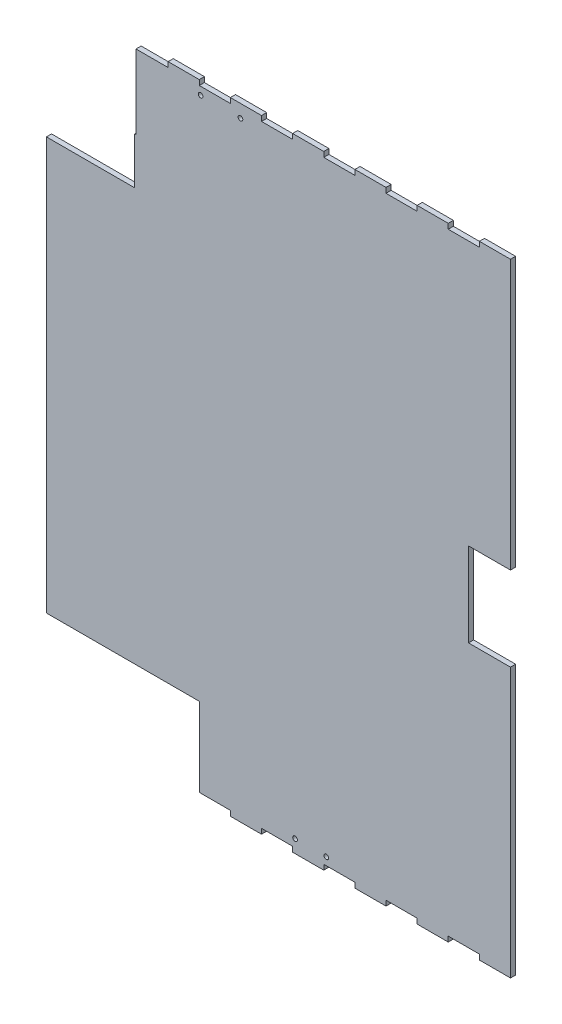
SolidWorks part; units mm, degrees
material "Balsa"
ref_plane "Front Plane" through (0, 0, 0) normal (0, 0, 1) x (1, 0, 0)
ref_plane "Top Plane" through (0, 0, 0) normal (0, 1, 0) x (1, 0, 0)
ref_plane "Right Plane" through (0, 0, 0) normal (1, 0, 0) x (0, 0, -1)
sketch "Sketch1" plane through (0, 0, 0) normal (0, 0, 1) x (1, 0, 0)
  line L0 (-5.7823, -13) -> (25.5, -13)
  line L2 (-5.7823, 1) -> (-5.7823, -13)
  line L5 (24.5, -14) -> (-24.5, -14) construction
  line L6 (323.7481, -265) -> (323.7481, 30)
  line L7 (-5.8246, -265) -> (65.6329, -265)
  line L8 (-5.8246, -265) -> (-5.8246, -225)
  line L11 (-5.8246, -265) -> (65.6329, -225) construction
  line L12 (-5.8246, -225) -> (65.6329, -265) construction
  line L15 (323.7481, -265) -> (25.5, -265)
  line L16 (25.5, 1) -> (25.5, -265)
  line L17 (-5.8246, -225) -> (25.5, -225)
  line L18 (-24.5, -224) -> (24.5, -224) construction
  line L19 (-5.7823, 1) -> (25.5, 1)
  line L20 (24.5, -224) -> (24.5, -14) construction
  line L21 (-85.1981, 31) -> (50.7481, 31) construction
  line L23 (25.5, 1) -> (25.5, 30)
  line L24 (25.5, 30) -> (323.7481, 30)
  line L27 (277.3251, 57) -> (277.3251, -295) construction
  line L28 (26.2777, -266) -> (-26.2882, -266) construction
  line L30 (-63.4467, 81) -> (255.5737, 81) construction
  line L31 (83.0863, 30) -> (323.7481, 30)
  line L32 (83.0863, 30) -> (83.0863, 77.7)
  line L33 (83.0863, 77.7) -> (323.7481, 77.7)
  line L34 (323.7481, 30) -> (323.7481, 77.7)
  line L35 (83.0863, 30) -> (323.7481, 77.7) construction
  line L36 (83.0863, 77.7) -> (323.7481, 30) construction
  line L37 (255.5737, -319) -> (-63.4467, -319) construction
  line L38 (323.7481, -265) -> (123.7481, -265)
  line L39 (323.7481, -265) -> (323.7481, -315.7)
  line L40 (323.7481, -315.7) -> (123.7481, -315.7)
  line L41 (123.7481, -265) -> (123.7481, -315.7)
  line L42 (323.7481, -265) -> (123.7481, -315.7) construction
  line L43 (323.7481, -315.7) -> (123.7481, -265) construction
  line L44 (50.7481, 31) -> (50.7481, -269) construction
  line L45 (83.0863, 31) -> (83.0863, -269) construction
  point P4 (32.4695, -6)
  point P10 (29.9042, -245)
  point P15 (48.1318, -132)
  point P24 (48.1318, 15.5)
  point P36 (203.4172, 53.85)
  point P42 (223.7481, -290.35)
  dimension "D1" = 1
  dimension "D2" = 1
  dimension "D3" = 1
  dimension "D4" = 1
  dimension "D5" = 1
  dimension "D6" = 31.3246
  dimension "D7" = 273
  dimension "D8" = 3.3
  dimension "D9" = 200
  dimension "D10" = 3.3
extrude "Boss-Extrude1" add sketch "Sketch1" along normal blind 3.3 contours L24 L23 L16 L7 L15 L6 | L15 L41 L40 L39 | L24 L34 L33 L32
sketch "Sketch2" plane through (0, 0, 0) normal (0, 0, -1) x (-1, 0, 0)
  circle A0 centre (-150.2163, 72.7) radius 1.5
  circle A1 centre (-124.6149, 72.7) radius 1.5
  circle A2 centre (-205.3942, -310.7) radius 1.5
  circle A3 centre (-185.3098, -310.7) radius 1.5
  circle A4 centre (-150.2163, 72.7) radius 2 construction
  circle A5 centre (-124.6149, 72.7) radius 2 construction
  circle A6 centre (-205.3942, -310.7) radius 2 construction
  circle A7 centre (-185.3098, -310.7) radius 2 construction
  dimension "D1" = 3
  dimension "D2" = 3
  dimension "D3" = 3
  dimension "D4" = 3
extrude "Cut-Extrude1" cut sketch "Sketch2" against normal through all
sketch "Sketch3" plane through (119.3915, 0, 256.0358) normal (0.4226, 0, 0.9063) x (0.9063, 0, -0.4226)
  line L1 (293.4595, -146) -> (268.9595, -146)
  line L2 (293.4595, -146) -> (293.4595, -92)
  line L3 (293.4595, -92) -> (268.9595, -92)
  line L4 (268.9595, -146) -> (268.9595, -92)
  line L5 (293.4595, -146) -> (268.9595, -92) construction
  line L6 (293.4595, -92) -> (268.9595, -146) construction
  point P4 (281.2095, -119)
extrude "Cut-Extrude2" cut sketch "Sketch3" against normal through all both and the other way through all
sketch "Sketch4" plane through (0, 0, 0) normal (0, 0, -1) x (-1, 0, 0)
  line L1 (-323.7481, -92) -> (-296.7639, -92)
  line L2 (-323.7481, -92) -> (-323.7481, -146)
  line L3 (-323.7481, -146) -> (-296.7639, -146)
  line L4 (-296.7639, -92) -> (-296.7639, -146)
  line L5 (-323.7481, -92) -> (-296.7639, -146) construction
  line L6 (-323.7481, -146) -> (-296.7639, -92) construction
  point P4 (-310.256, -119)
extrude "Cut-Extrude3" cut sketch "Sketch4" against normal blind 10
sketch "Sketch6" plane through (0, 0, 3.3) normal (0, 0, 1) x (1, 0, 0)
  line L1 (25.5, 30) -> (82.2279, 30)
  line L2 (25.5, 30) -> (25.5, 0)
  line L3 (25.5, 0) -> (82.2279, 0)
  line L4 (82.2279, 30) -> (82.2279, 0)
  line L5 (25.5, 30) -> (82.2279, 0) construction
  line L6 (25.5, 0) -> (82.2279, 30) construction
  point P4 (53.864, 15)
extrude "Cut-Extrude4" cut sketch "Sketch6" against normal blind 10
sketch "Sketch7" plane through (0, 0, 0) normal (0, 0, -1) x (-1, 0, 0)
  line L0 (-203.7481, -315.7) -> (-183.7481, -315.7)
  line L1 (-163.7481, -315.7) -> (-143.7481, -315.7)
  line L2 (-163.7481, -315.7) -> (-163.7481, -319)
  line L3 (-163.7481, -319) -> (-143.7481, -319)
  line L4 (-143.7481, -315.7) -> (-143.7481, -319)
  line L5 (-163.7481, -315.7) -> (-143.7481, -319) construction
  line L6 (-163.7481, -319) -> (-143.7481, -315.7) construction
  line L7 (-103.7481, 77.7) -> (-123.7481, 77.7)
  line L8 (-103.7481, 77.7) -> (-103.7481, 81)
  line L9 (-103.7481, 81) -> (-123.7481, 81)
  line L10 (-123.7481, 77.7) -> (-123.7481, 81)
  line L11 (-103.7481, 77.7) -> (-123.7481, 81) construction
  line L12 (-103.7481, 81) -> (-123.7481, 77.7) construction
  line L13 (-203.7481, -315.7) -> (-203.7481, -319)
  line L14 (-203.7481, -319) -> (-183.7481, -319)
  line L15 (-183.7481, -315.7) -> (-183.7481, -319)
  line L16 (-143.7481, 77.7) -> (-163.7481, 77.7)
  line L17 (-143.7481, 77.7) -> (-143.7481, 81)
  line L18 (-143.7481, 81) -> (-163.7481, 81)
  line L19 (-163.7481, 77.7) -> (-163.7481, 81)
  line L20 (-203.7481, -315.7) -> (-183.7481, -319) construction
  line L21 (-203.7481, -319) -> (-183.7481, -315.7) construction
  line L22 (-143.7481, 77.7) -> (-163.7481, 81) construction
  line L23 (-143.7481, 81) -> (-163.7481, 77.7) construction
  line L24 (-243.7481, -315.7) -> (-223.7481, -315.7)
  line L25 (-243.7481, -315.7) -> (-243.7481, -319)
  line L26 (-243.7481, -319) -> (-223.7481, -319)
  line L27 (-223.7481, -315.7) -> (-223.7481, -319)
  line L28 (-183.7481, 77.7) -> (-203.7481, 77.7)
  line L29 (-183.7481, 77.7) -> (-183.7481, 81)
  line L30 (-183.7481, 81) -> (-203.7481, 81)
  line L31 (-203.7481, 77.7) -> (-203.7481, 81)
  line L32 (-243.7481, -315.7) -> (-223.7481, -319) construction
  line L33 (-243.7481, -319) -> (-223.7481, -315.7) construction
  line L34 (-183.7481, 77.7) -> (-203.7481, 81) construction
  line L35 (-183.7481, 81) -> (-203.7481, 77.7) construction
  line L36 (-283.7481, -315.7) -> (-263.7481, -315.7)
  line L37 (-283.7481, -315.7) -> (-283.7481, -319)
  line L38 (-283.7481, -319) -> (-263.7481, -319)
  line L39 (-263.7481, -315.7) -> (-263.7481, -319)
  line L40 (-223.7481, 77.7) -> (-243.7481, 77.7)
  line L41 (-223.7481, 77.7) -> (-223.7481, 81)
  line L42 (-223.7481, 81) -> (-243.7481, 81)
  line L43 (-243.7481, 77.7) -> (-243.7481, 81)
  line L44 (-283.7481, -315.7) -> (-263.7481, -319) construction
  line L45 (-283.7481, -319) -> (-263.7481, -315.7) construction
  line L46 (-223.7481, 77.7) -> (-243.7481, 81) construction
  line L47 (-223.7481, 81) -> (-243.7481, 77.7) construction
  line L48 (-323.7481, -315.7) -> (-303.7481, -315.7)
  line L49 (-323.7481, -315.7) -> (-323.7481, -319)
  line L50 (-323.7481, -319) -> (-303.7481, -319)
  line L51 (-303.7481, -315.7) -> (-303.7481, -319)
  line L52 (-263.7481, 77.7) -> (-283.7481, 77.7)
  line L53 (-263.7481, 77.7) -> (-263.7481, 81)
  line L54 (-263.7481, 81) -> (-283.7481, 81)
  line L55 (-283.7481, 77.7) -> (-283.7481, 81)
  line L56 (-323.7481, -315.7) -> (-303.7481, -319) construction
  line L57 (-323.7481, -319) -> (-303.7481, -315.7) construction
  line L58 (-263.7481, 77.7) -> (-283.7481, 81) construction
  line L59 (-263.7481, 81) -> (-283.7481, 77.7) construction
  line L60 (-143.7481, -315.7) -> (-143.7481, -319) construction
  line L61 (-303.7481, 77.7) -> (-323.7481, 77.7)
  line L62 (-303.7481, 77.7) -> (-303.7481, 81)
  line L63 (-303.7481, 81) -> (-323.7481, 81)
  line L64 (-323.7481, 77.7) -> (-323.7481, 81)
  line L65 (-303.7481, 77.7) -> (-323.7481, 81) construction
  line L66 (-303.7481, 81) -> (-323.7481, 77.7) construction
  point P4 (-193.7481, -317.35)
  point P11 (-113.7481, 79.35)
  point P19 (-233.7481, -317.35)
  point P24 (-153.7481, 79.35)
  point P29 (-273.7481, -317.35)
  point P34 (-193.7481, 79.35)
  point P39 (-313.7481, -317.35)
  point P44 (-233.7481, 79.35)
  point P49 (-353.7481, -317.35)
  point P54 (-273.7481, 79.35)
  point P62 (-313.7481, 79.35)
  dimension "D1" = 5
  dimension "D2" = 2
extrude "Boss-Extrude2" add sketch "Sketch7" against normal blind 3.3
